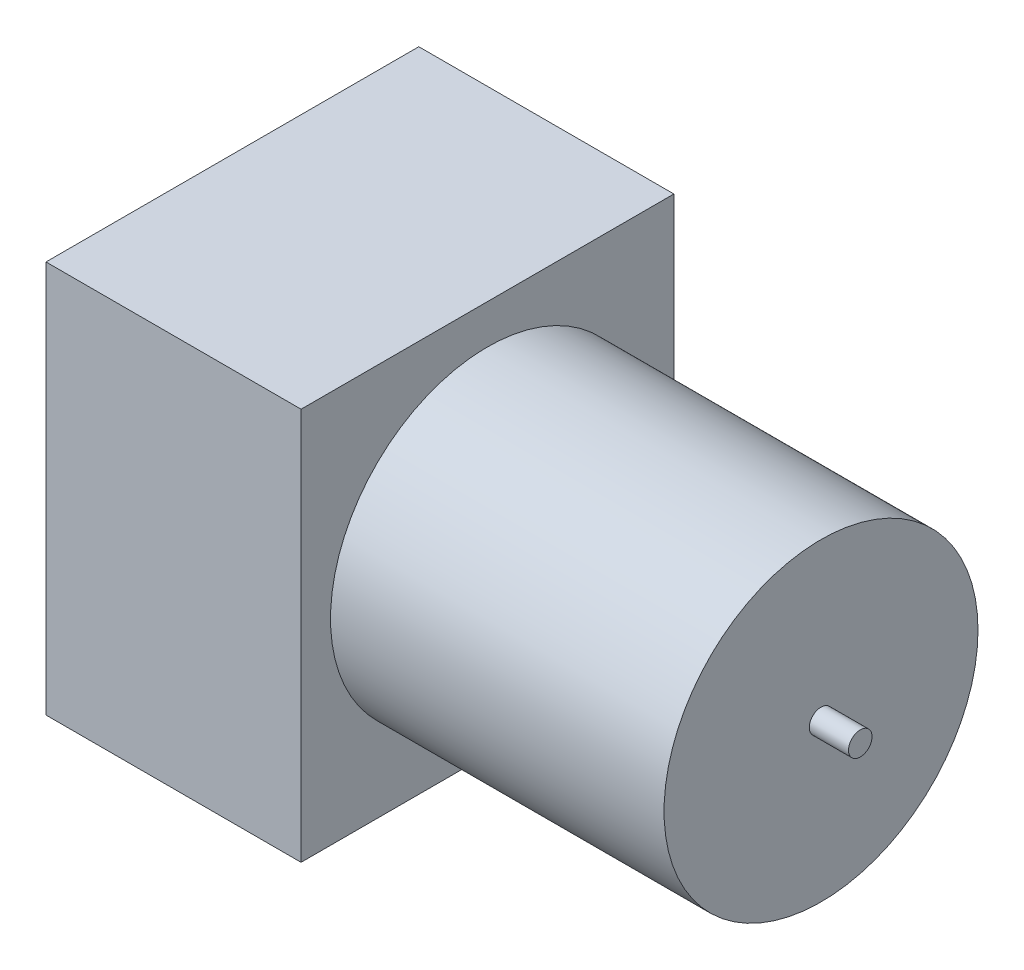
SolidWorks part; units mm, degrees
ref_plane "Front Plane" through (0, 0, 0) normal (0, 0, 1) x (1, 0, 0)
ref_plane "Top Plane" through (0, 0, 0) normal (0, 1, 0) x (1, 0, 0)
ref_plane "Right Plane" through (0, 0, 0) normal (1, 0, 0) x (0, 0, -1)
other "Configuration Table"
sketch "Sketch1" plane through (0, 0, 0) normal (0, 1, 0) x (1, 0, 0)
  line L1 (0, -47.5) -> (65, -47.5)
  line L2 (0, -47.5) -> (0, 47.5)
  line L3 (0, 47.5) -> (65, 47.5)
  line L4 (65, -47.5) -> (65, 47.5)
  line L5 (0, -47.5) -> (65, 47.5) construction
  line L6 (0, 47.5) -> (65, -47.5) construction
  point P5 (32.5, 0)
  dimension "D1" = 65
  dimension "D2" = 95
extrude "Pump_Head" add sketch "Sketch1" along normal blind 100
sketch "Sketch2" plane through (0, 0, 0) normal (1, 0, 0) x (0, 0, -1)
  circle A0 centre (0, 50) radius 40
  dimension "D1" = 80
extrude "Motor" add sketch "Sketch2" along normal blind 85 from offset 65
sketch "Sketch3" plane through (0, 0, 0) normal (1, 0, 0) x (0, 0, -1)
  circle A0 centre (0, 30) radius 6
  dimension "D1" = 12
extrude "Inlet_Port" add sketch "Sketch3" along normal blind 12 from offset 12
sketch "Sketch4" plane through (0, 0, 0) normal (1, 0, 0) x (0, 0, -1)
  circle A0 centre (0, 30) radius 3.2
  dimension "D1" = 6.4
extrude "Inlet_Socket" cut sketch "Sketch4" along normal blind 10 from offset 12
sketch "Sketch5" plane through (0, 0, 0) normal (1, 0, 0) x (0, 0, -1)
  circle A0 centre (0, 70) radius 6
  dimension "D1" = 12
extrude "Outlet_Port" add sketch "Sketch5" along normal blind 12 from offset 12
sketch "Sketch6" plane through (0, 0, 0) normal (1, 0, 0) x (0, 0, -1)
  circle A0 centre (0, 70) radius 3.2
  dimension "D1" = 6.4
extrude "Outlet_Socket" cut sketch "Sketch6" along normal blind 10 from offset 12
sketch "Sketch7" plane through (0, 0, 0) normal (1, 0, 0) x (0, 0, -1)
  circle A0 centre (0, 50) radius 3
  dimension "D1" = 6
extrude "Cable_Stub" add sketch "Sketch7" along normal blind 10 from offset 150
equation "\"Jar_OD\"= 90  'ASSUMED - Part G fallback - jar outer diameter"
equation "\"Jar_H\"= 120  'ASSUMED - Part G fallback - jar height"
equation "\"Pump_L\"= 45  'ASSUMED - Part G fallback"
equation "\"Pump_W\"= 24  'ASSUMED - Part G fallback"
equation "\"Pump_H\"= 33  'ASSUMED - Part G fallback"
equation "\"Pump_Outlet_OD\"= 7.5  'ASSUMED - Part G fallback"
equation "\"Tube_OD\"= 8  'ASSUMED - Part G fallback"
equation "\"Tube_ID\"= 6  'ASSUMED - Part G fallback"
equation "\"TDS_Body_Dia\"= 12  'ASSUMED - Part G fallback"
equation "\"TDS_Wet_Len\"= 45  'ASSUMED - Part G fallback - length in water"
equation "\"DS_Tube_Dia\"= 6  'ASSUMED - Part G fallback"
equation "\"DS_Tube_Len\"= 50  'ASSUMED - Part G fallback"
equation "\"ORP_Body_Dia\"= 12  'ASSUMED - Part G fallback"
equation "\"ORP_Body_Len\"= 150  'ASSUMED - Part G fallback"
equation "\"ORP_Cap_Dia\"= 16  'ASSUMED - Part G fallback"
equation "\"Turb_W\"= 33  'ASSUMED - Part G fallback - head width"
equation "\"Turb_D\"= 28  'ASSUMED - Part G fallback - head depth"
equation "\"Turb_H\"= 30  'ASSUMED - Part G fallback - head height"
equation "\"Turb_Slot_W\"= 10  'ASSUMED - Part G fallback - slot width"
equation "\"Flow_L\"= 62  'ASSUMED - Part G fallback YF-S201"
equation "\"Flow_W\"= 36  'ASSUMED - Part G fallback"
equation "\"Flow_H\"= 35  'ASSUMED - Part G fallback"
equation "\"Thread_G12_OD\"= 20.955  'ASSUMED - Part G fallback thread G1/2 (major diameter)"
equation "\"Valve_L\"= 75  'ASSUMED - Part G fallback"
equation "\"Valve_W\"= 45  'ASSUMED - Part G fallback"
equation "\"Valve_H\"= 60  'ASSUMED - Part G fallback"
equation "\"Tee_L\"= 40  'ASSUMED - Part G fallback - overall length"
equation "\"Tee_Branch_L\"= 25  'ASSUMED - Part G fallback"
equation "\"Tee_OD\"= 12  'ASSUMED - Part G fallback"
equation "\"LED_Board_L\"= 20  'ASSUMED - Part G fallback"
equation "\"LED_Board_W\"= 20  'ASSUMED - Part G fallback - LED at centre"
equation "\"GUVA_L\"= 20  'ASSUMED - Part G fallback"
equation "\"GUVA_W\"= 12  'ASSUMED - Part G fallback - sensor at centre"
equation "\"Reed_L\"= 27  'ASSUMED - Part G fallback MC-38 half"
equation "\"Reed_W\"= 14  'ASSUMED - Part G fallback"
equation "\"Reed_H\"= 8  'ASSUMED - Part G fallback"
equation "\"ESP_L\"= 51  'ASSUMED - Part G fallback"
equation "\"ESP_W\"= 28  'ASSUMED - Part G fallback"
equation "\"TFT_L\"= 58  'ASSUMED - Part G fallback - board"
equation "\"TFT_W\"= 35  'ASSUMED - Part G fallback - board"
equation "\"TFT_Win_L\"= 35  'ASSUMED - Part G fallback - visible window"
equation "\"TFT_Win_W\"= 28  'ASSUMED - Part G fallback - visible window"
equation "\"Relay_L\"= 50  'ASSUMED - Part G fallback"
equation "\"Relay_W\"= 26  'ASSUMED - Part G fallback"
equation "\"Relay_H\"= 19  'ASSUMED - Part G fallback"
equation "\"Mosfet_L\"= 34  'ASSUMED - Part G fallback"
equation "\"Mosfet_W\"= 17  'ASSUMED - Part G fallback"
equation "\"Mosfet_H\"= 12  'ASSUMED - Part G fallback"
equation "\"TDS_Board_L\"= 42  'ASSUMED - Part G fallback"
equation "\"TDS_Board_W\"= 32  'ASSUMED - Part G fallback"
equation "\"Turb_Board_L\"= 38  'ASSUMED - Part G fallback"
equation "\"Turb_Board_W\"= 28  'ASSUMED - Part G fallback"
equation "\"BNC_Thread_Dia\"= 9.5  'ASSUMED - Part G fallback"
equation "\"Plate_L\"= 420  'ASSUMED - Part G fallback"
equation "\"Plate_W\"= 297  'ASSUMED - Part G fallback"
equation "\"Plate_T\"= 6  'ASSUMED - Part G fallback"
equation "\"Booster_L\"= 150  'ASSUMED - Part G fallback - booster pump"
equation "\"Booster_W\"= 95  'ASSUMED - Part G fallback"
equation "\"Booster_H\"= 100  'ASSUMED - Part G fallback"
equation "\"PTube_OD\"= 6.35  'ASSUMED - Part G fallback - product tube 1/4 inch"
equation "\"Qz_Out\"= 12  'ASSUMED - Part G fallback - quartz channel outside square"
equation "\"Qz_Path\"= 10  'ASSUMED - Part G fallback - quartz channel inside light path"
equation "\"Qz_L\"= 40  'ASSUMED - Part G fallback - quartz channel length"
equation "\"LED860_Dia\"= 5  'ASSUMED - Part G fallback - 860 nm LED"
equation "\"BPW_L\"= 5.4  'ASSUMED - Part G fallback - BPW34"
equation "\"BPW_W\"= 4.3  'ASSUMED - Part G fallback - BPW34"
equation "\"Cart_Dia\"= 50  'ASSUMED - Part G fallback - sediment and pre-carbon cartridges"
equation "\"Cart_L\"= 255  'ASSUMED - Part G fallback"
equation "\"UF_Dia\"= 50  'ASSUMED - Part G fallback - UF cartridge"
equation "\"UF_L\"= 260  'ASSUMED - Part G fallback"
equation "\"RO_Dia\"= 62  'ASSUMED - Part G fallback - RO membrane housing"
equation "\"RO_L\"= 300  'ASSUMED - Part G fallback"
equation "\"UVC_Dia\"= 40  'ASSUMED - Part G fallback - UV-C chamber"
equation "\"UVC_L\"= 300  'ASSUMED - Part G fallback"
equation "\"Tank_W\"= 260  'ASSUMED - Part G fallback - storage tank"
equation "\"Tank_D\"= 160  'ASSUMED - Part G fallback"
equation "\"Tank_H\"= 300  'ASSUMED - Part G fallback"
equation "\"Cab_W\"= 400  'ASSUMED - Part G fallback - purifier cabinet"
equation "\"Cab_D\"= 270  'ASSUMED - Part G fallback"
equation "\"Cab_H\"= 560  'ASSUMED - Part G fallback"
equation "\"ORP_Board_L\"= 40  'ASSUMED - Part G fallback - ORP buffer board"
equation "\"ORP_Board_W\"= 30  'ASSUMED - Part G fallback"
equation "\"Opt_Board_L\"= 50  'ASSUMED - Part G fallback - optical front-end board"
equation "\"Opt_Board_W\"= 40  'ASSUMED - Part G fallback"
equation "\"Buck_L\"= 43  'ASSUMED - Part G fallback - 12 V to 5 V buck module"
equation "\"Buck_W\"= 21  'ASSUMED - Part G fallback"
equation "\"Buck_H\"= 14  'ASSUMED - Part G fallback"
equation "\"BB_L\"= 165  'ASSUMED - Part G fallback - breadboard (As_Built_R3 only)"
equation "\"BB_W\"= 55  'ASSUMED - Part G fallback"
equation "\"BB_H\"= 10  'ASSUMED - Part G fallback"
equation "\"Cuv_W\"= 12.5  'ASSUMED - old R3 cuvette (station suppressed in SS4)"
equation "\"Cuv_D\"= 12.5  'ASSUMED - old R3 cuvette (station suppressed in SS4)"
equation "\"Cuv_H\"= 45  'ASSUMED - old R3 cuvette (station suppressed in SS4)"
equation "\"Probe_Clr\"= 0.3  'DESIGN VALUE - Part C rule 3 - printed probe hole = diameter + 0.3"
equation "\"Label_H\"= 0.6  'DESIGN VALUE - Part D - raised label height"
equation "\"D2@Sketch1\" = \"Booster_W\""
equation "\"D1@Pump_Head\" = \"Booster_H\""
